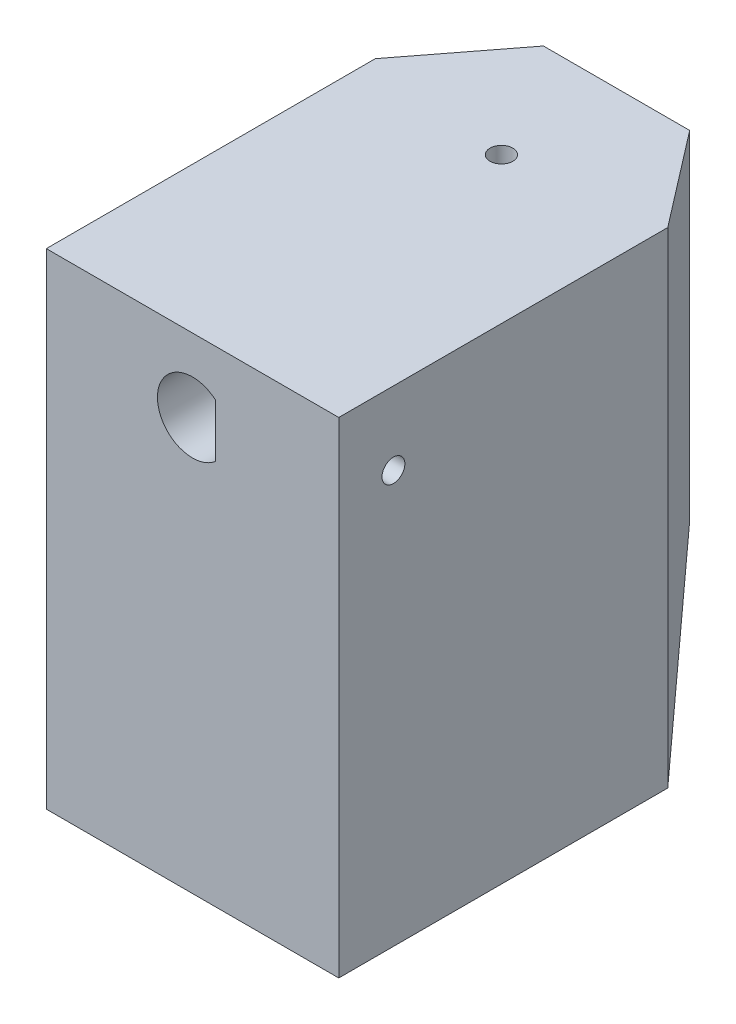
SolidWorks part; units mm, degrees
ref_plane "Front Plane" through (0, 0, 0) normal (0, 0, 1) x (1, 0, 0)
ref_plane "Top Plane" through (0, 0, 0) normal (0, 1, 0) x (1, 0, 0)
ref_plane "Right Plane" through (0, 0, 0) normal (1, 0, 0) x (0, 0, -1)
sketch "Sketch2" plane through (0, 0, 0) normal (0, 0, 1) x (1, 0, 0)
  line L0 (12.7, -6.35) -> (14.2875, -6.35)
  line L1 (-14.2875, 6.35) -> (14.2875, 6.35)
  line L2 (-14.2875, 6.35) -> (-14.2875, -6.35)
  line L3 (-14.2875, -6.35) -> (-12.7, -6.35)
  line L4 (14.2875, 6.35) -> (14.2875, -6.35)
  line L6 (-12.7, -6.35) -> (-12.7, -35.814)
  line L7 (-12.7, -35.814) -> (12.7, -35.814)
  line L8 (12.7, -6.35) -> (12.7, -35.814)
  point P5 (0, 6.35)
  point P7 (14.2875, 0)
  point P13 (0, -35.814)
  dimension "D1" = 28.575
  dimension "D2" = 12.7
  dimension "D3" = 42.164
  dimension "D4" = 25.4
extrude "Boss-Extrude1" add sketch "Sketch2" along normal blind 25.4 contours L4 L1 L2 L3 | L8 L3 L6 L7
sketch "Sketch3" plane through (0, 0, 25.4) normal (0, 0, 1) x (1, 0, 0)
  line L0 (2.0031, 2.3) -> (2.0031, -2.3)
  arc A0 (2.0031, 2.3) -> (2.0031, -2.3) centre (0, 0) ccw
  point P1 (2.0053, -2.3019)
  dimension "D1" = 6.1
  dimension "D2" = 4.6
extrude "Cut-Extrude1" cut sketch "Sketch3" against normal blind 9.5
sketch "Sketch5" plane through (0, 0, 0) normal (0, 0, -1) x (-1, 0, 0)
  line L0 (14.2875, 6.35) -> (-14.2875, 6.35) construction
  line L1 (-12.7, 6.35) -> (12.7, 6.35)
  line L2 (-12.7, 6.35) -> (-12.7, -35.814)
  line L3 (-12.7, -35.814) -> (12.7, -35.814)
  line L4 (12.7, 6.35) -> (12.7, -35.814)
  line L5 (12.7, -6.35) -> (12.7, -35.814) construction
  line L6 (-12.7, -6.35) -> (-12.7, -35.814) construction
  dimension "D1" = 42.164
extrude "Boss-Extrude2" add sketch "Sketch5" along normal blind 11.43
sketch "Sketch6" plane through (12.7, 0, 0) normal (1, 0, 0) x (0, 0, -1)
  line L0 (3.175, -35.814) -> (11.43, -23.0188)
  line L1 (-25.4, -35.814) -> (11.43, -35.814) construction
  line L2 (11.43, 6.35) -> (11.43, -35.814) construction
  line L3 (11.43, -23.0188) -> (11.43, -35.814)
  line L4 (11.43, -35.814) -> (3.175, -35.814)
  dimension "D1" = 3.175
  dimension "D2" = 23.0188
extrude "Cut-Extrude2" cut sketch "Sketch6" against normal up to next
sketch "Sketch7" plane through (0, -35.814, 0) normal (0, -1, 0) x (1, 0, 0)
  line L0 (-12.7, -11.43) -> (-12.7, -3.175)
  line L1 (-12.7, -3.175) -> (-6.35, -11.43)
  line L2 (-12.7, -11.43) -> (12.7, -11.43) construction
  line L3 (-6.35, -11.43) -> (-12.7, -11.43)
  line L4 (6.35, -11.43) -> (12.7, -3.175)
  line L5 (12.7, -3.175) -> (12.7, -11.43)
  line L6 (12.7, -11.43) -> (6.35, -11.43)
  line L7 (-6.35, -11.43) -> (6.35, -11.43) construction
  point P10 (0, -11.43)
  dimension "D1" = 12.7
extrude "Cut-Extrude3" cut sketch "Sketch7" against normal up to next
sketch "Sketch8" plane through (0, 0, -11.43) normal (0, 0, -1) x (-1, 0, 0)
  line L0 (-1.651, 2.8596) -> (1.651, 2.8596)
  arc A0 (-1.651, 2.8596) -> (1.651, 2.8596) centre (0, 0) ccw
  dimension "D1" = 6.604
  dimension "D2" = 3.302
extrude "Cut-Extrude4" cut sketch "Sketch8" against normal blind 20
sketch "Sketch10" plane through (0, -35.814, 0) normal (0, -1, 0) x (1, 0, 0)
  line L0 (-12.7, 25.4) -> (12.7, 25.4) construction
  line L1 (-9.525, 22.225) -> (9.525, 22.225)
  line L2 (-9.525, 22.225) -> (-9.525, 3.175)
  line L3 (-9.525, 3.175) -> (9.525, 3.175)
  line L4 (9.525, 22.225) -> (9.525, 3.175)
  line L5 (12.7, 25.4) -> (12.7, -3.175) construction
  line L6 (12.7, 0) -> (14.2875, 0) construction
  point P6 (0, 22.225)
  dimension "D1" = 3.175
  dimension "D2" = 3.175
  dimension "D3" = 3.175
extrude "Cut-Extrude5" cut sketch "Sketch10" against normal offset from surface (26.289 mm away) 3.175 up to face at (13.4938, -6.35, 12.7)
sketch "Sketch11" plane through (0, 0, 25.4) normal (0, 0, 1) x (1, 0, 0)
  line L1 (-14.2875, 6.35) -> (-12.7, 6.35)
  line L2 (-14.2875, 6.35) -> (-14.2875, -6.35)
  line L3 (-14.2875, -6.35) -> (-12.7, -6.35)
  line L4 (-12.7, 6.35) -> (-12.7, -6.35)
  line L5 (12.7, -6.35) -> (14.2875, -6.35)
  line L6 (12.7, -6.35) -> (12.7, 6.35)
  line L7 (12.7, 6.35) -> (14.2875, 6.35)
  line L8 (14.2875, -6.35) -> (14.2875, 6.35)
extrude "Cut-Extrude6" cut sketch "Sketch11" against normal up to next
sketch "Sketch12" plane through (12.7, 0, 0) normal (1, 0, 0) x (0, 0, -1)
  line L1 (-25.4, 0) -> (0, 0) construction
  line L2 (-25.4, -2.3) -> (-25.4, 2.3) construction
  line L3 (-15.9, 0) -> (-25.4, 0) construction
  circle A0 centre (-20.65, 0) radius 0.9922
  point P6 (-25.4, 0)
  point P7 (0, 0)
  point P9 (0, 0)
  dimension "D1" = 1.9844
extrude "Cut-Extrude7" cut sketch "Sketch12" against normal through all
sketch "Sketch13" plane through (0, 6.35, 0) normal (0, 1, 0) x (1, 0, 0)
  line L1 (0, -8.57) -> (0, 11.43) construction
  circle A0 centre (0, 1.43) radius 0.9922
  point P2 (0, 0)
  dimension "D1" = 1.9844
extrude "Cut-Extrude8" cut sketch "Sketch13" against normal up to next
